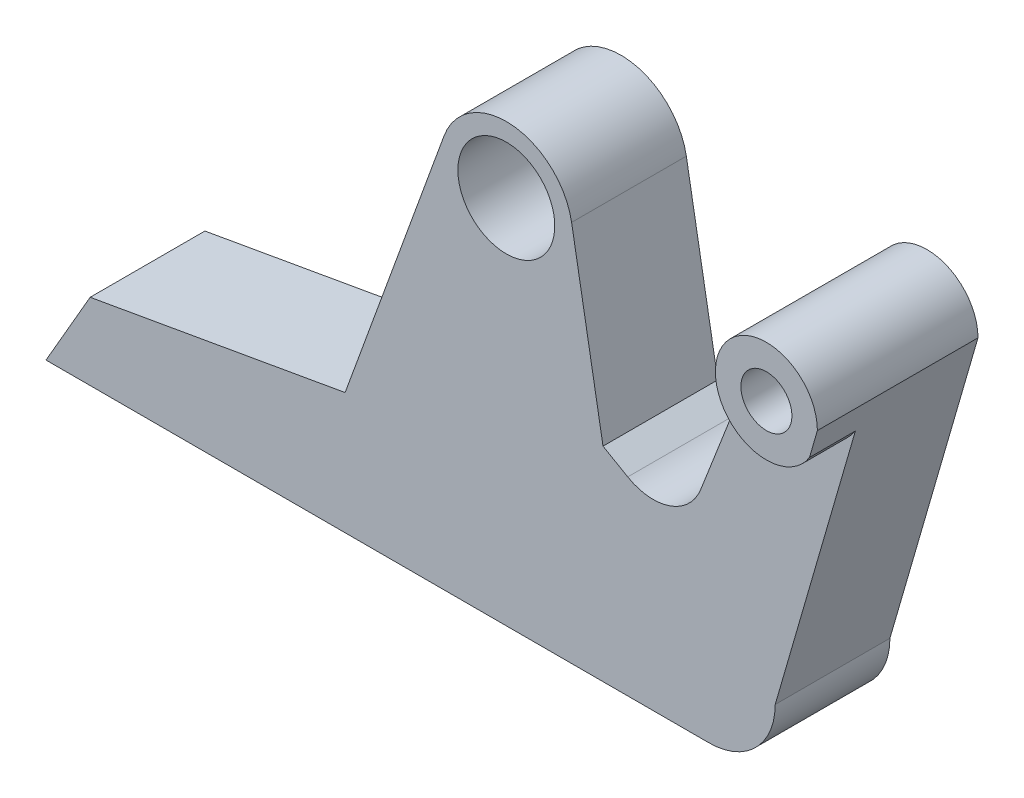
SolidWorks part; units mm, degrees
ref_plane "Front Plane" through (0, 0, 0) normal (0, 0, 1) x (1, 0, 0)
ref_plane "Top Plane" through (0, 0, 0) normal (0, 1, 0) x (1, 0, 0)
ref_plane "Right Plane" through (0, 0, 0) normal (1, 0, 0) x (0, 0, -1)
sketch "Sketch1" plane through (0, 0, 0) normal (0, 0, 1) x (1, 0, 0)
  line L0 (78.0582, 77.1119) -> (58.6603, 23.8163)
  line L5 (103.0768, 74.9231) -> (109.2346, 40)
  line L6 (58.6603, 23.8163) -> (8.6603, 15)
  line L7 (8.6603, 15) -> (0, 0)
  line L8 (0, 0) -> (130, 0)
  line L9 (109.2346, 40) -> (136.5, 24.2583)
  line L10 (140.2742, 72.6656) -> (117, 13)
  line L12 (160.2742, 72.6656) -> (143, 13)
  line L14 (90.2742, 72.6656) -> (219.4605, 72.6656) construction
  circle A0 centre (90.2742, 72.6656) radius 13
  circle A1 centre (130, 13) radius 13
  circle A2 centre (90.2742, 72.6656) radius 9.5
  circle A3 centre (130, 13) radius 3.5 construction
  circle A4 centre (150.2742, 72.6656) radius 10
  circle A5 centre (150.2742, 72.6656) radius 5
  dimension "D3" = 26
  dimension "D4" = 26
  dimension "D5" = 19
  dimension "D6" = 7
  dimension "D14" = 20
  dimension "D15" = 10
  dimension "D1" = 60
  dimension "D2" = 10
  dimension "D7" = 50
  dimension "D8" = 15
  dimension "D9" = 130
  dimension "D10" = 30
  dimension "D11" = 40
  dimension "D12" = 70
  dimension "D13" = 80
  dimension "D16" = 60
extrude "Boss-Extrude1" add sketch "Sketch1" along normal blind 22.5 contours A1 L10 L9 L5 A0 L0 L6 L7 L8 | A0 A2 | A1 L9 L10 | A1 L10 | A4 L10 L9 A1 L12 | L12 A4 A5
ref_plane "Plane1" through (0, 0, 0) normal (-1, 0, 0) x (0, 0, -1)
sketch "Sketch6" plane through (0, 0, 0) normal (-1, 0, 0) x (0, 0, -1)
  line L0 (-22.5, 0) -> (0, 0) construction
  line L1 (-14.25, 0) -> (-8.25, 0)
  line L2 (-14.25, 0) -> (-14.25, -3)
  line L3 (-14.25, -3) -> (-8.25, -3)
  line L4 (-8.25, 0) -> (-8.25, -3)
  line L5 (-11.25, 0) -> (-11.25, -8.4365) construction
  line L6 (-17.25, -3) -> (-5.25, -3)
  line L7 (-17.25, -3) -> (-17.25, -6)
  line L8 (-17.25, -6) -> (-5.25, -6)
  line L9 (-5.25, -3) -> (-5.25, -6)
  point P6 (-11.25, 0)
  point P8 (-11.25, 0)
  point P14 (-11.25, -6)
  dimension "D1" = 3
  dimension "D2" = 6
  dimension "D3" = 12
  dimension "D4" = 3
extrude "Cut-Extrude2" cut sketch "Sketch6" against normal up to vertex (130 mm away) contours L1 L5 L6 L4 | L6 L5 L8 L9 | L5 L1 L2 L3 | L5 L3 L6 L7 L8
fillet "Fillet1" radius 10 1 edges at (124.1688, 31.3778, 11.25)
sketch "Sketch7" plane through (0, 0, 22.5) normal (0, 0, 1) x (1, 0, 0)
  circle A0 centre (150.2742, 72.6656) radius 5
  circle A1 centre (150.2742, 72.6656) radius 10
  circle A2 centre (150.2742, 72.6656) radius 5 construction
  arc A3 (160.2742, 72.6656) -> (140.2742, 72.6656) centre (150.2742, 72.6656) ccw construction
  line M4 (143, 13) -> (160.2742, 72.6656)
  arc M5 (160.2742, 72.6656) -> (140.2742, 72.6656) centre (150.2742, 72.6656) ccw
  circle M16 centre (150.2742, 72.6656) radius 5
extrude "Boss-Extrude2" add sketch "Sketch7" along normal blind 9 contours A1 M5 M4 M16
